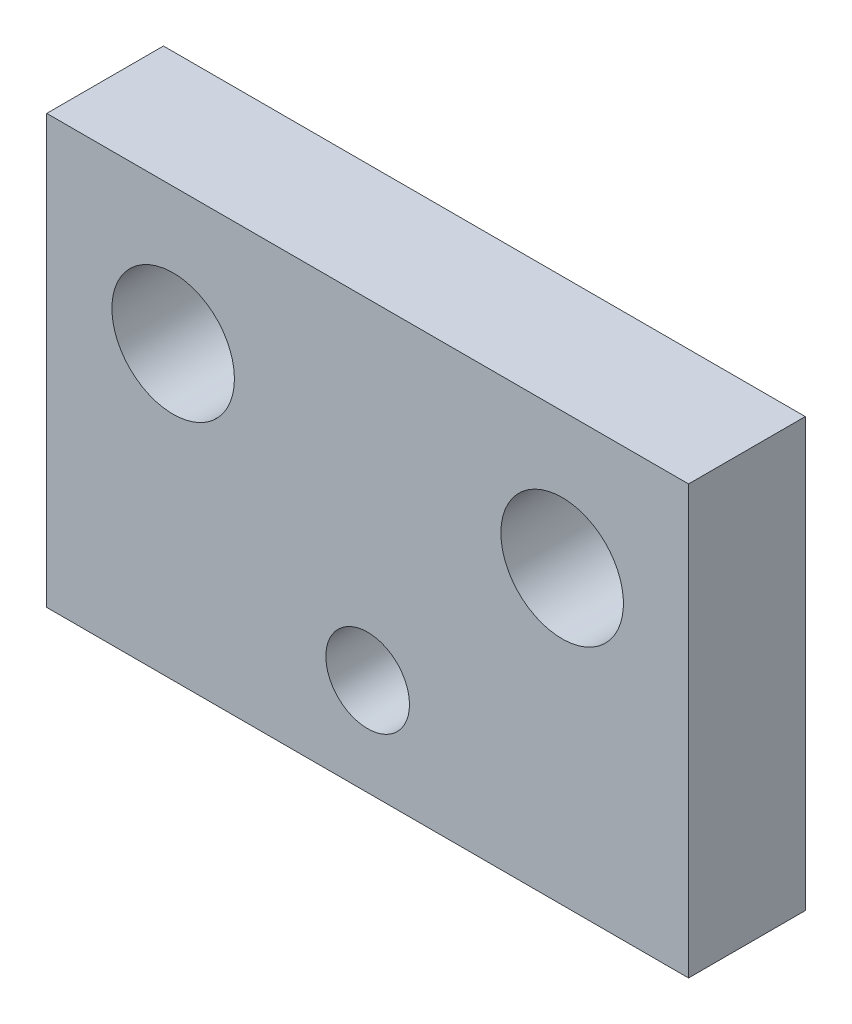
SolidWorks part; units mm, degrees
ref_plane "前视基准面" through (0, 0, 0) normal (0, 0, 1) x (1, 0, 0)
ref_plane "上视基准面" through (0, 0, 0) normal (0, 1, 0) x (1, 0, 0)
ref_plane "右视基准面" through (0, 0, 0) normal (1, 0, 0) x (0, 0, -1)
sketch "草图1" plane through (0, 0, 0) normal (0, 0, 1) x (1, 0, 0)
  line L1 (-16.5, 22) -> (16.5, 22)
  line L2 (-16.5, 22) -> (-16.5, 0)
  line L3 (-16.5, 0) -> (16.5, 0)
  line L4 (16.5, 22) -> (16.5, 0)
  line L5 (-16.5, 22) -> (16.5, 0) construction
  line L6 (-16.5, 0) -> (16.5, 22) construction
  point P0 (0, 11)
  dimension "D1" = 22
  dimension "D2" = 33
extrude "凸台-拉伸1" add sketch "草图1" along normal blind 6
sketch "草图2" plane through (0, 0, 0) normal (0, 0, 1) x (1, 0, 0)
  line L0 (0, 2.6455) -> (0, 15.3376) construction
  line L1 (-16.5, 22) -> (-16.5, 0) construction
  circle A0 centre (-10, 15) radius 3.15
  circle A1 centre (0, 5) radius 2.15
  circle A2 centre (10, 15) radius 3.15
  dimension "D1" = 6.3
  dimension "D3" = 4.3
  dimension "D2" = 20
  dimension "D4" = 5
  dimension "D5" = 15
  dimension "D6" = 16.5
extrude "切除-拉伸1" cut sketch "草图2" along normal blind 6
cosmetic thread "装饰螺纹线1" parameters "D2"=5
